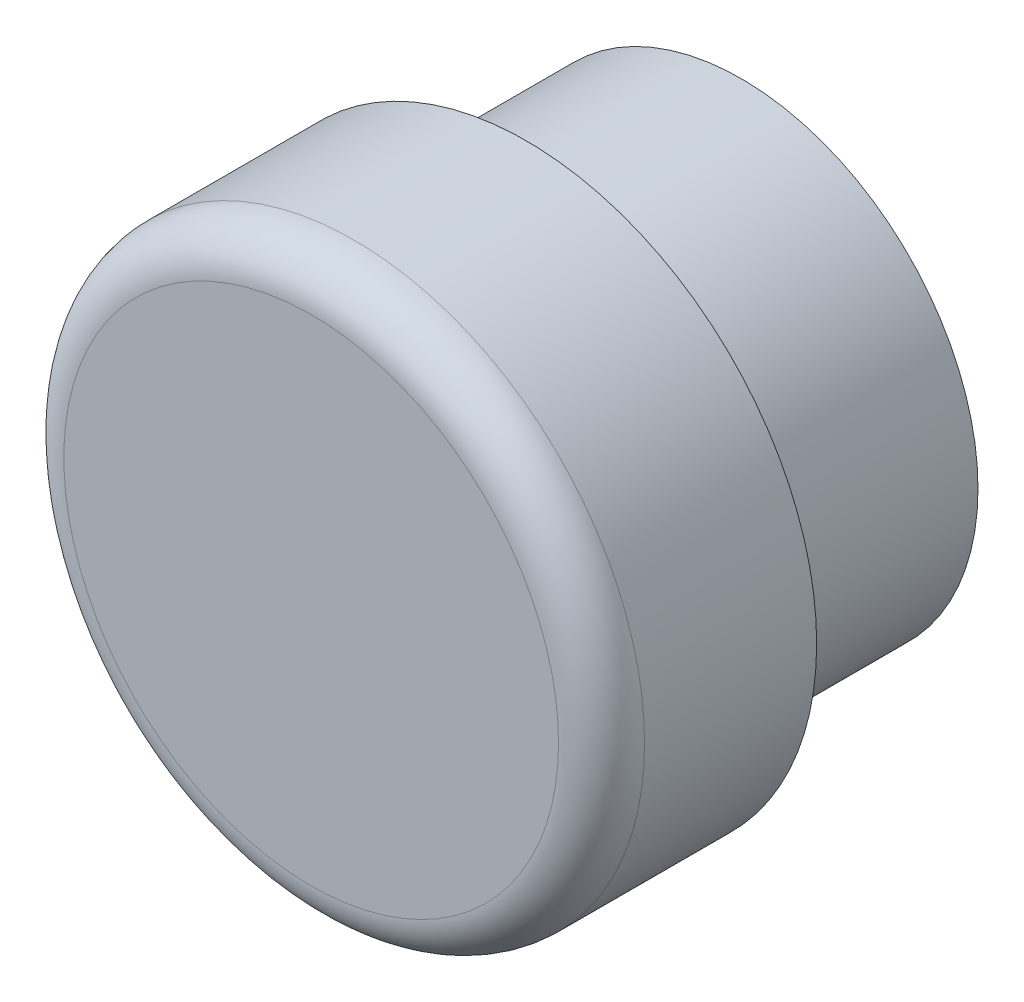
SolidWorks part; units mm, degrees
ref_plane "Front Plane" through (0, 0, 0) normal (0, 0, 1) x (1, 0, 0)
ref_plane "Top Plane" through (0, 0, 0) normal (0, 1, 0) x (1, 0, 0)
ref_plane "Right Plane" through (0, 0, 0) normal (1, 0, 0) x (0, 0, -1)
sketch "Sketch1" plane through (0, 0, 0) normal (0, 0, 1) x (1, 0, 0)
  circle A0 centre (0, 0) radius 11
  dimension "D1" = 22
extrude "Boss-Extrude1" add sketch "Sketch1" along normal blind 10
sketch "Sketch2" plane through (0, 0, 10) normal (0, 0, 1) x (1, 0, 0)
  circle A0 centre (0, 0) radius 13.5
  dimension "D1" = 27
extrude "Boss-Extrude2" add sketch "Sketch2" along normal blind 10
fillet "Fillet1" radius 2 1 edges at (13.5, 0, 20)
